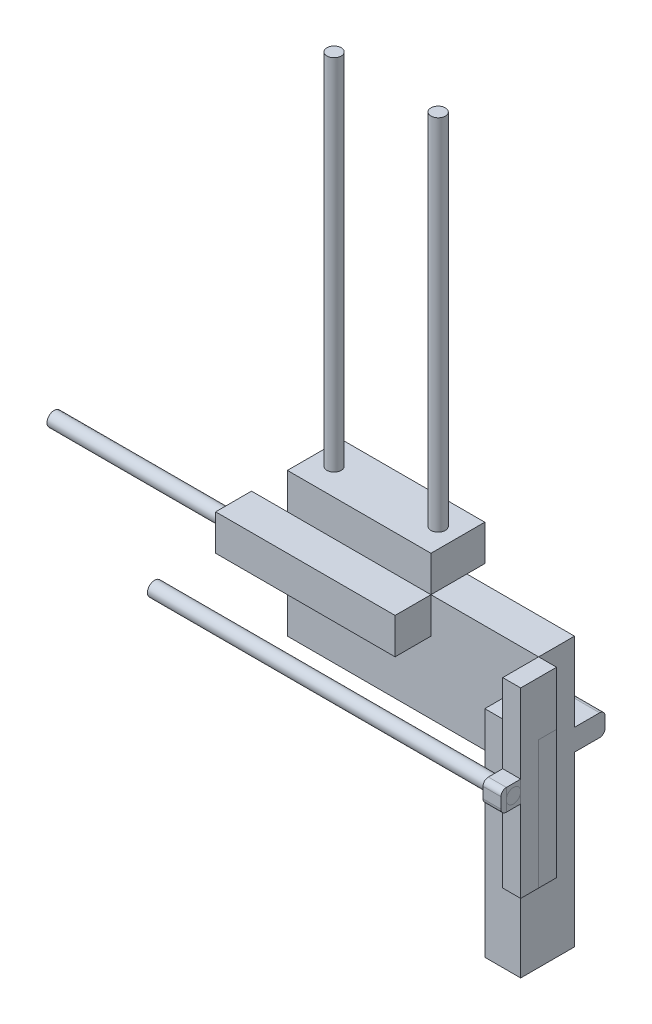
SolidWorks part; units mm, degrees
ref_plane "Front Plane" through (0, 0, 0) normal (0, 0, 1) x (1, 0, 0)
ref_plane "Top Plane" through (0, 0, 0) normal (0, 1, 0) x (1, 0, 0)
ref_plane "Right Plane" through (0, 0, 0) normal (1, 0, 0) x (0, 0, -1)
sketch "Sketch1" plane through (0, 0, 0) normal (0, 1, 0) x (1, 0, 0)
  line L1 (-5, 7.5) -> (5, 7.5)
  line L2 (-5, 7.5) -> (-5, -7.5)
  line L3 (-5, -7.5) -> (5, -7.5)
  line L4 (5, 7.5) -> (5, -7.5)
  line L5 (-5, 7.5) -> (5, -7.5) construction
  line L6 (-5, -7.5) -> (5, 7.5) construction
  point P0 (0, 0)
  dimension "D1" = 15
  dimension "D2" = 10
extrude "Boss-Extrude1" add sketch "Sketch1" along normal blind 60
ref_plane "Plane1" through (-5, 0, 0) normal (1, 0, 0) x (0, 0, -1)
sketch "Sketch2" plane through (-5, 0, 0) normal (1, 0, 0) x (0, 0, -1)
  line L0 (7.5, 60) -> (-2.5, 60)
  line L1 (7.5, 60) -> (-7.5, 60) construction
  line L2 (7.5, 60) -> (7.5, 45)
  line L3 (7.5, 60) -> (7.5, 0) construction
  line L4 (-2.5, 60) -> (-2.5, 45)
  line L5 (-2.5, 45) -> (7.5, 45)
  dimension "D1" = 10
  dimension "D2" = 15
extrude "Boss-Extrude2" add sketch "Sketch2" against normal blind 60
ref_plane "Plane2" through (0, 60, 0) normal (0, 1, 0) x (1, 0, 0)
sketch "Sketch3" plane through (0, 60, 0) normal (0, 1, 0) x (1, 0, 0)
  line L0 (-65, -2.5) -> (5, -2.5)
  line L1 (5, -7.5) -> (5, 7.5) construction
  line L2 (5, -2.5) -> (5, 7.5)
  line L3 (5, 7.5) -> (-65, 7.5)
  line L4 (-65, 7.5) -> (-65, -2.5)
extrude "Boss-Extrude3" add sketch "Sketch3" along normal blind 15
ref_plane "Plane3" through (5, 75, 2.5) normal (0, 0, -1) x (-1, 0, 0)
ref_plane "Plane4" through (0, 75, 0) normal (0, 1, 0) x (1, 0, 0)
sketch "Sketch6" plane through (0, 75, 0) normal (0, 1, 0) x (1, 0, 0)
  line L0 (-65, -2.5) -> (-25, -2.5)
  line L1 (-65, -2.5) -> (-65, 12.5)
  line L2 (-25, -2.5) -> (-25, 12.5)
  line L3 (-65, 12.5) -> (-25, 12.5)
  line L4 (-65, -2.5) -> (5, -2.5) construction
  dimension "D1" = 40
  dimension "D2" = 15
extrude "Boss-Extrude4" add sketch "Sketch6" along normal blind 10
ref_plane "Plane5" through (0, 85, 0) normal (0, 1, 0) x (1, 0, 0)
sketch "Sketch7" plane through (0, 85, 0) normal (0, 1, 0) x (1, 0, 0)
  line L0 (-45, 12.5) -> (-45, -2.5)
  line L1 (-25, 12.5) -> (-65, 12.5) construction
  line L2 (-65, -2.5) -> (-25, -2.5) construction
  line L3 (-59.5, 5) -> (-30.5, 5)
  circle A0 centre (-30.5, 5) radius 2
  circle A1 centre (-59.5, 5) radius 2
  point P9 (-45, 5)
  dimension "D2" = 4
  dimension "D1" = 29
extrude "Boss-Extrude5" add sketch "Sketch7" along normal blind 100
sketch "Sketch8" plane through (5, 75, 2.5) normal (0, 0, -1) x (-1, 0, 0)
  line L2 (30, 0) -> (30, -10)
  line L3 (30, 0) -> (80, 0)
  line L4 (80, -10) -> (80, 0)
  line L6 (70, -10) -> (30, -10)
  line L7 (70, -10) -> (80, -10)
extrude "Boss-Extrude6" add sketch "Sketch8" against normal blind 10 contours L4 L3 L2 L6 L7
ref_plane "Plane6" through (5, 0, 0) normal (1, 0, 0) x (0, 0, -1)
sketch "Sketch10" plane through (5, 0, 0) normal (1, 0, 0) x (0, 0, -1)
  line L0 (-2.5, 74.2056) -> (-2.5, 24.2056)
  line L1 (-2.5, 74.2056) -> (-12.5, 74.2056)
  line L2 (-2.5, 24.2056) -> (-12.5, 24.2056)
  line L3 (-12.5, 74.2056) -> (-12.5, 24.2056)
  line L4 (-2.5, 75) -> (-2.5, 60) construction
  line L5 (-2.5, 60) -> (-7.5, 60)
  line L6 (-7.5, 60) -> (-7.5, 24.2056)
  line L7 (-7.5, 24.2056) -> (-2.5, 24.2056)
  dimension "D1" = 50
  dimension "D2" = 10
extrude "Boss-Extrude12" add sketch "Sketch10" along normal blind 5 contours L5 L6 L2 L0
sketch "Sketch11" plane through (5, 0, 0) normal (1, 0, 0) x (0, 0, -1)
  line L0 (-2.5, 75) -> (-12.5, 75)
  line L1 (-7.5, 24.2056) -> (-2.5, 24.2056)
  line L2 (-2.5, 24.2056) -> (-12.5, 24.2056)
  line L3 (-12.5, 24.2056) -> (-12.5, 75)
  line L4 (-2.5, 75) -> (-2.5, 60)
  line L5 (-2.5, 60) -> (-7.5, 60)
  line L6 (-7.5, 60) -> (-7.5, 24.2056)
  dimension "D1" = 10
extrude "Boss-Extrude15" add sketch "Sketch11" along normal blind 5 separate body contours L6 L5 L4 L0 L3 L2
ref_plane "Plane7" through (5, 75, 12.5) normal (0, 0, -1) x (-1, 0, 0)
sketch "Sketch12" plane through (5, 75, 12.5) normal (0, 0, -1) x (-1, 0, 0)
  line L0 (-5, -50.7944) -> (-5, -35.7944)
  line L1 (-5, -50.7944) -> (-5, 0) construction
  dimension "D1" = 15
ref_plane "Plane8" through (10, 0, 0) normal (1, 0, 0) x (0, 0, -1)
sketch "Sketch14" plane through (10, 0, 0) normal (1, 0, 0) x (0, 0, -1)
sketch "Sketch19" plane through (5, 0, 0) normal (1, 0, 0) x (0, 0, -1)
  line L0 (7.5, 75) -> (7.5, 50)
  line L1 (7.5, 75) -> (7.5, 0) construction
  line L2 (7.5, 50) -> (12.5, 50)
  circle A0 centre (12.5, 50) radius 2
  dimension "D3" = 4
  dimension "D1" = 25
  dimension "D2" = 5
extrude "Boss-Extrude18" add sketch "Sketch19" against normal blind 150 separate body
sketch "Sketch20" plane through (5, 0, 0) normal (1, 0, 0) x (0, 0, -1)
  line L0 (7.5, 75) -> (7.5, 50)
  line L1 (7.5, 75) -> (7.5, 0) construction
  line L2 (7.5, 50) -> (12.5, 50)
  line L6 (12.5, 53.0024) -> (7.5, 53.0024)
  line L7 (12.5, 46.9976) -> (7.5, 46.9976)
  line L8 (7.5, 46.9976) -> (7.5, 53.0024)
  line L10 (14.5, 53.0024) -> (12.5, 53.0024)
  line L12 (14.5, 46.9976) -> (12.5, 46.9976)
  line L13 (16.0012, 48.4988) -> (16.0012, 51.5012)
  arc A3 (14.5, 53.0024) -> (16.0012, 51.5012) centre (14.5, 51.5012) cw
  arc A4 (14.5, 46.9976) -> (16.0012, 48.4988) centre (14.5, 48.4988) ccw
  point P11 (12.5, 50)
  dimension "D1" = 25
extrude "Boss-Extrude19" add sketch "Sketch20" against normal blind 10
sketch "Sketch26" plane through (10, 0, 0) normal (1, 0, 0) x (0, 0, -1)
  line L0 (-12.5, 75) -> (-12.5, 50)
  line L1 (-12.5, 24.2056) -> (-12.5, 75) construction
  line L2 (-12.5, 50) -> (-14.5, 50)
  circle A0 centre (-14.5, 50) radius 2
  dimension "D1" = 25
  dimension "D2" = 2
extrude "Boss-Extrude22" add sketch "Sketch26" against normal blind 100 separate body
sketch "Sketch27" plane through (10, 0, 0) normal (1, 0, 0) x (0, 0, -1)
sketch "Sketch29" plane through (5, 0, 0) normal (1, 0, 0) x (0, 0, -1)
sketch "Sketch33" plane through (10, 0, 0) normal (1, 0, 0) x (0, 0, -1)
  line L0 (-12.5, 75) -> (-12.5, 50)
  line L1 (-12.5, 24.2056) -> (-12.5, 75) construction
  line L2 (-12.5, 50) -> (-16.5, 50)
  line L3 (-16.5, 50) -> (-16.5, 53)
  line L4 (-16.5, 50) -> (-16.5, 47)
  line L5 (-18, 48.5) -> (-18, 51.5)
  line L6 (-16.5, 53) -> (-12.5, 53)
  line L7 (-12.5, 53) -> (-12.5, 47)
  line L8 (-12.5, 47) -> (-16.5, 47)
  circle A0 centre (-14.5, 50) radius 2 construction
  arc A1 (-16.5, 53) -> (-18, 51.5) centre (-16.5, 51.5) ccw
  arc A2 (-16.5, 47) -> (-18, 48.5) centre (-16.5, 48.5) cw
  circle A3 centre (-14.5, 50) radius 2
  dimension "D1" = 3
  dimension "D2" = 3
extrude "Boss-Extrude31" add sketch "Sketch33" against normal blind 5 separate body contours A3 L0 L6 L3 | A3 L4 L8 L7
sketch "Sketch36" plane through (10, 0, 0) normal (1, 0, 0) x (0, 0, -1)
  line L0 (-16.5, 50) -> (-16.5, 53) construction
  line L1 (-16.5, 50) -> (-16.5, 47) construction
  line L2 (-18, 48.5) -> (-18, 51.5)
  line L3 (-16.5, 53) -> (-16.5, 47)
  arc A0 (-16.5, 53) -> (-18, 51.5) centre (-16.5, 51.5) ccw
  arc A1 (-16.5, 47) -> (-18, 48.5) centre (-16.5, 48.5) cw
extrude "Boss-Extrude33" add sketch "Sketch36" against normal blind 5 separate body contours L3 A1 L2 A0
